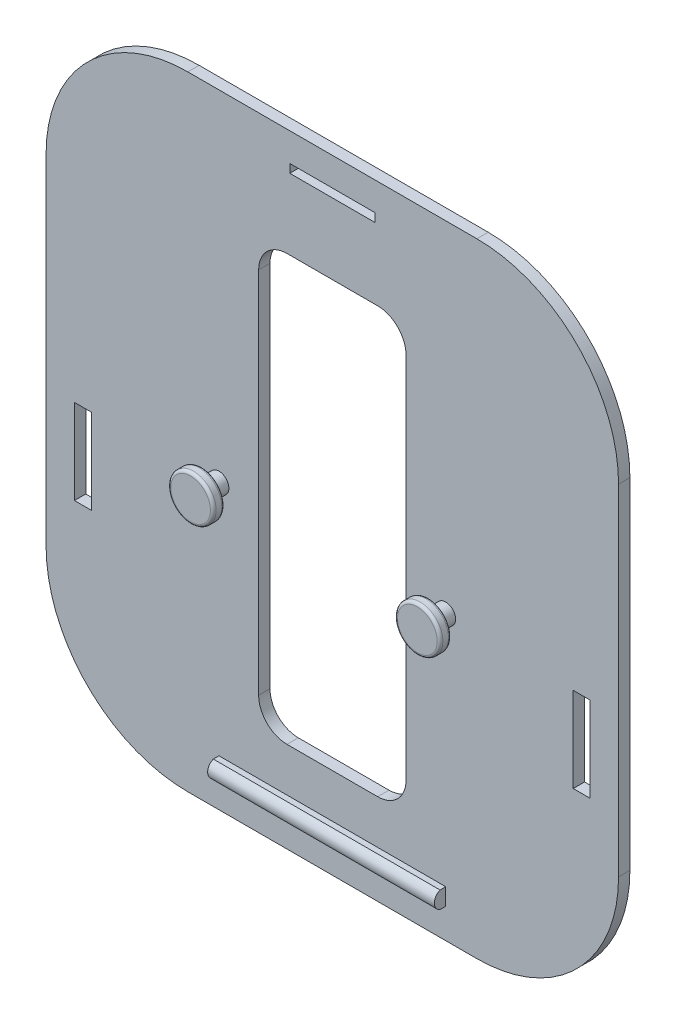
SolidWorks part; units mm, degrees
material "PE Low/Medium Density"
ref_plane "Front Plane" through (0, 0, 0) normal (0, 0, 1) x (1, 0, 0)
ref_plane "Top Plane" through (0, 0, 0) normal (0, 1, 0) x (1, 0, 0)
ref_plane "Right Plane" through (0, 0, 0) normal (1, 0, 0) x (0, 0, -1)
sketch "Sketch1" plane through (0, 0, 0) normal (0, 0, 1) x (1, 0, 0)
  line L0 (48, 82.1) -> (37, 82.1) construction
  line L1 (-8, 87.1) -> (93, 87.1)
  line L2 (-8, 87.1) -> (-8, -22.9)
  line L3 (-8, -22.9) -> (93, -22.9)
  line L4 (93, 87.1) -> (93, -22.9)
  line L5 (88, 11.6) -> (88, -12.4009) construction
  line L6 (-3, 26.6) -> (-3, 40.6) construction
  dimension "D1" = 5
  dimension "D2" = 5
  dimension "D3" = 5
  dimension "D4" = 110
extrude "Boss-Extrude1" add sketch "Sketch1" along normal blind 2
sketch "Sketch3" plane through (0, 0, 2) normal (0, 0, 1) x (1, 0, 0)
  line L1 (35, 82.1) -> (50, 82.1)
  line L2 (35, 82.1) -> (35, 80.6)
  line L3 (35, 80.6) -> (50, 80.6)
  line L4 (50, 82.1) -> (50, 80.6)
  line L5 (-3, 26.6) -> (0, 26.6)
  line L6 (-3, 26.6) -> (-3, 11.6)
  line L7 (-3, 11.6) -> (0, 11.6)
  line L8 (0, 26.6) -> (0, 11.6)
  line L9 (85, 26.6) -> (88, 26.6)
  line L10 (85, 26.6) -> (85, 11.6)
  line L11 (85, 11.6) -> (88, 11.6)
  line L12 (88, 26.6) -> (88, 11.6)
extrude "Cut-Extrude1" cut sketch "Sketch3" against normal through all
sketch "Sketch4" plane through (0, 0, 2) normal (0, 0, 1) x (1, 0, 0)
  line L0 (22.5, 27.1) -> (62.5, 27.1) construction
  line L1 (42.5, 27.1) -> (42.5, -22.9) construction
  line L2 (-8, -22.9) -> (93, -22.9) construction
  circle A0 centre (22.5, 27.1) radius 1.75
  circle A1 centre (62.5, 27.1) radius 1.75
  dimension "D2" = 3.5
  dimension "D1" = 40
  dimension "D3" = 50
extrude "Boss-Extrude2" add sketch "Sketch4" along normal blind 5
sketch "Sketch5" plane through (0, 0, 7) normal (0, 0, 1) x (1, 0, 0)
  circle A0 centre (22.5, 27.1) radius 4
  circle A1 centre (62.5, 27.1) radius 4
  dimension "D1" = 8
extrude "Boss-Extrude3" add sketch "Sketch5" against normal blind 2
fillet "Fillet1" radius 0.5 4 edges at (26.5, 27.1, 5) (26.5, 27.1, 7) (66.5, 27.1, 5) (66.5, 27.1, 7)
fillet "Fillet2" radius 25 4 edges at (93, 87.1, 1) (93, -22.9, 1) (-8, -22.9, 1) (-8, 87.1, 1)
sketch "Sketch6" plane through (0, 0, 2) normal (0, 0, 1) x (1, 0, 0)
  line L0 (42.5, -17.65) -> (42.5, -22.9) construction
  line L1 (22.5, -14.65) -> (62.5, -14.65)
  line L2 (22.5, -14.65) -> (22.5, -17.65)
  line L3 (22.5, -17.65) -> (62.5, -17.65)
  line L4 (62.5, -14.65) -> (62.5, -17.65)
  line L5 (17, -22.9) -> (68, -22.9) construction
  circle A0 centre (22.5, 27.1) radius 1.75 construction
  dimension "D1" = 40
  dimension "D2" = 3
  dimension "D3" = 40
extrude "Boss-Extrude4" add sketch "Sketch6" along normal blind 1
sketch "Sketch7" plane through (62.5, 0, 0) normal (1, 0, 0) x (0, 0, -1)
  line L0 (-3, -17.65) -> (-3, -14.65) construction
  line L1 (-3, -14.65) -> (-3, -17.65)
  arc A0 (-3, -14.65) -> (-3, -17.65) centre (-2.375, -16.15) ccw
  dimension "D1" = 1
extrude "Boss-Extrude5" add sketch "Sketch7" against normal up to surface (40 mm away) up to face at (22.5, -16.15, 2.5)
sketch "Sketch9" plane through (0, 0, 2) normal (0, 0, 1) x (1, 0, 0)
  line L1 (29.5, 68.1) -> (55.5, 68.1)
  line L2 (29.5, 68.1) -> (29.5, -6.9)
  line L3 (29.5, -6.9) -> (55.5, -6.9)
  line L4 (55.5, 68.1) -> (55.5, -6.9)
  circle A0 centre (22.5, 27.1) radius 4 construction
  circle A1 centre (62.5, 27.1) radius 4 construction
  dimension "D1" = 3
  dimension "D2" = 3
  dimension "D4" = 30
  dimension "D3" = 75
extrude "Cut-Extrude2" cut sketch "Sketch9" against normal through all
fillet "Fillet3" radius 5 4 edges at (29.5, -6.9, 1) (55.5, -6.9, 1) (55.5, 68.1, 1) (29.5, 68.1, 1)
